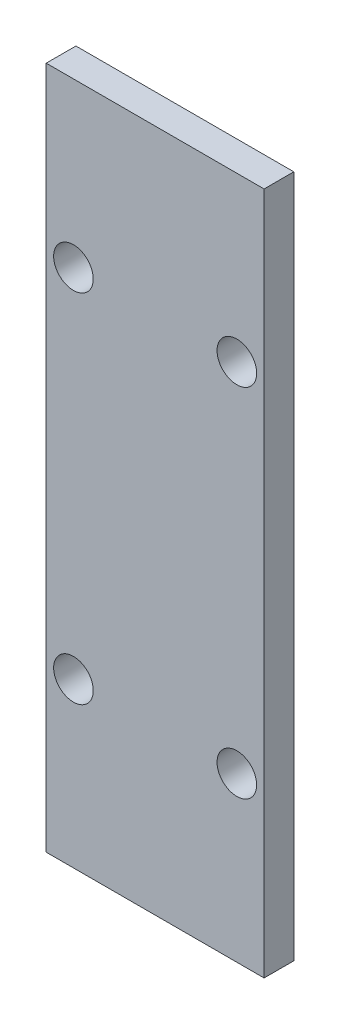
SolidWorks part; units mm, degrees
material "环氧树脂,未充填"
ref_plane "前视基准面" through (0, 0, 0) normal (0, 0, 1) x (1, 0, 0)
ref_plane "上视基准面" through (0, 0, 0) normal (0, 1, 0) x (1, 0, 0)
ref_plane "右视基准面" through (0, 0, 0) normal (1, 0, 0) x (0, 0, -1)
sketch "草图1" plane through (0, 0, 0) normal (0, 0, 1) x (1, 0, 0)
  line L1 (-11, 34.5) -> (11, 34.5)
  line L2 (-11, 34.5) -> (-11, -34.5)
  line L3 (-11, -34.5) -> (11, -34.5)
  line L4 (11, 34.5) -> (11, -34.5)
  line L5 (-11, 34.5) -> (11, -34.5) construction
  line L6 (-11, -34.5) -> (11, 34.5) construction
  point P0 (0, 0)
  dimension "D1" = 69
  dimension "D2" = 22
extrude "凸台-拉伸1" add sketch "草图1" along normal blind 3
sketch "草图2" plane through (0, 0, 3) normal (0, 0, 1) x (1, 0, 0)
  line L1 (-8.25, 18) -> (8.25, 18) construction
  line L2 (-8.25, 18) -> (-8.25, -18) construction
  line L3 (-8.25, -18) -> (8.25, -18) construction
  line L4 (8.25, 18) -> (8.25, -18) construction
  line L5 (-8.25, 18) -> (8.25, -18) construction
  line L6 (-8.25, -18) -> (8.25, 18) construction
  circle A0 centre (-8.25, 18) radius 2
  circle A1 centre (8.25, 18) radius 2
  circle A2 centre (8.25, -18) radius 2
  circle A3 centre (-8.25, -18) radius 2
  point P0 (0, 0)
  dimension "D1" = 36
  dimension "D3" = 4
  dimension "D2" = 16.5
extrude "切除-拉伸1" cut sketch "草图2" against normal through all
